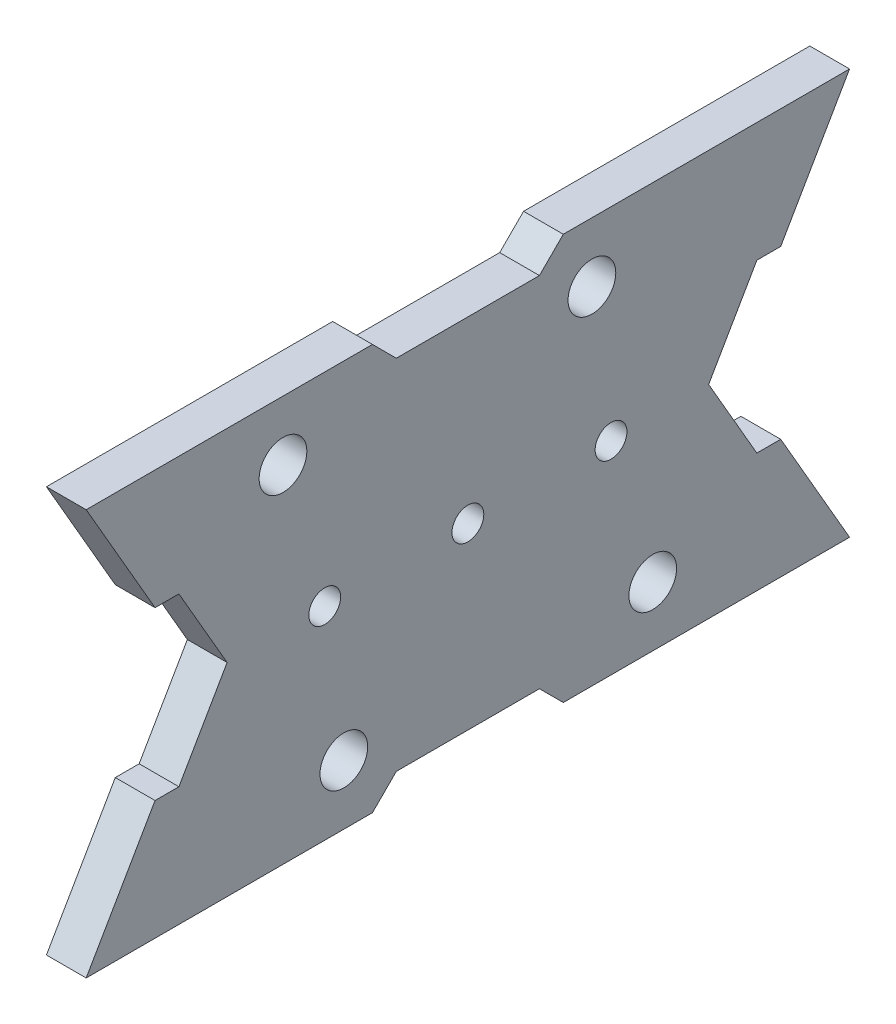
SolidWorks part; units mm, degrees
ref_plane "Front Plane" through (0, 0, 0) normal (0, 0, 1) x (1, 0, 0)
ref_plane "Top Plane" through (0, 0, 0) normal (0, 1, 0) x (1, 0, 0)
ref_plane "Right Plane" through (0, 0, 0) normal (1, 0, 0) x (0, 0, -1)
sketch "Sketch1" plane through (0, 0, 0) normal (1, 0, 0) x (0, 0, -1)
  line L0 (0, 0) -> (38.8489, 0) construction
  line L1 (38.8489, 0) -> (31.1969, 36) construction
  line L2 (31.1969, 36) -> (-7.652, 36) construction
  line L3 (-7.652, 36) -> (0, 0) construction
  line L4 (-1.2941, 37.3514) -> (6.358, 1.3514) construction
  line L5 (24.8389, 34.6486) -> (32.491, -1.3514) construction
  line L6 (-32.4015, -7.5) -> (3.5985, -7.5)
  line L7 (3.5985, -7.5) -> (6.5985, -4.5)
  line L8 (6.5985, -4.5) -> (24.5985, -4.5)
  line L9 (24.5985, -4.5) -> (27.5985, -7.5)
  line L10 (27.5985, -7.5) -> (63.5985, -7.5)
  line L11 (63.5985, -7.5) -> (54.9382, 7.5)
  line L12 (54.9382, 7.5) -> (51.9382, 7.5)
  line L13 (51.9382, 7.5) -> (45.876, 18)
  line L14 (45.876, 18) -> (51.9382, 28.5)
  line L15 (51.9382, 28.5) -> (54.9382, 28.5)
  line L16 (54.9382, 28.5) -> (63.5985, 43.5)
  line L17 (63.5985, 43.5) -> (27.5985, 43.5)
  line L18 (27.5985, 43.5) -> (24.5985, 40.5)
  line L19 (24.5985, 40.5) -> (6.5985, 40.5)
  line L20 (6.5985, 40.5) -> (3.5985, 43.5)
  line L21 (3.5985, 43.5) -> (-32.4015, 43.5)
  line L22 (-32.4015, 43.5) -> (-23.7413, 28.5)
  line L23 (-23.7413, 28.5) -> (-20.7413, 28.5)
  line L26 (-20.7413, 7.5) -> (-23.7413, 7.5)
  line L27 (-23.7413, 7.5) -> (-32.4015, -7.5)
  line L28 (-3.826, 18) -> (35.0229, 18) construction
  line L29 (19.4245, 0) -> (11.7724, 36) construction
  line L30 (-32.4015, 43.5) -> (-32.4015, -7.5) construction
  line L33 (-20.7413, 28.5) -> (-14.6791, 18)
  line L34 (-14.6791, 18) -> (-20.7413, 7.5)
  line L35 (15.5985, -4.5) -> (15.5985, 40.5) construction
  circle A0 centre (0, 0) radius 3
  circle A1 centre (38.8489, 0) radius 3
  circle A2 centre (31.1969, 36) radius 3
  circle A3 centre (-7.652, 36) radius 3
  circle A4 centre (0, 0) radius 6.5 construction
  circle A5 centre (0, 0) radius 7.5 construction
  circle A6 centre (38.8489, 0) radius 6.5 construction
  circle A7 centre (38.8489, 0) radius 7.5 construction
  circle A8 centre (31.1969, 36) radius 6.5 construction
  circle A9 centre (31.1969, 36) radius 7.5 construction
  circle A10 centre (-7.652, 36) radius 6.5 construction
  circle A11 centre (-7.652, 36) radius 7.5 construction
  circle A12 centre (15.5985, 18) radius 2
  circle A15 centre (-2.4015, 18) radius 2
  circle A16 centre (33.5985, 18) radius 2
  point P47 (15.5985, 18)
  dimension "D2" = 6
  dimension "D3" = 13
  dimension "D4" = 15
  dimension "D7" = 45
  dimension "D19" = 4
  dimension "D21" = 18
  dimension "D22" = 18
  dimension "D5" = 25
  dimension "D6" = 36
  dimension "D8" = 3
  dimension "D9" = 24
  dimension "D10" = 96
  dimension "D11" = 3
  dimension "D12" = 60
  dimension "D13" = 60
  dimension "D14" = 60
  dimension "D15" = 15
  dimension "D16" = 15
  dimension "D17" = 60
  dimension "D18" = 3
  dimension "D20" = 45
  dimension "D23" = 78
extrude "Boss-Extrude1" add sketch "Sketch1" along normal blind 5
